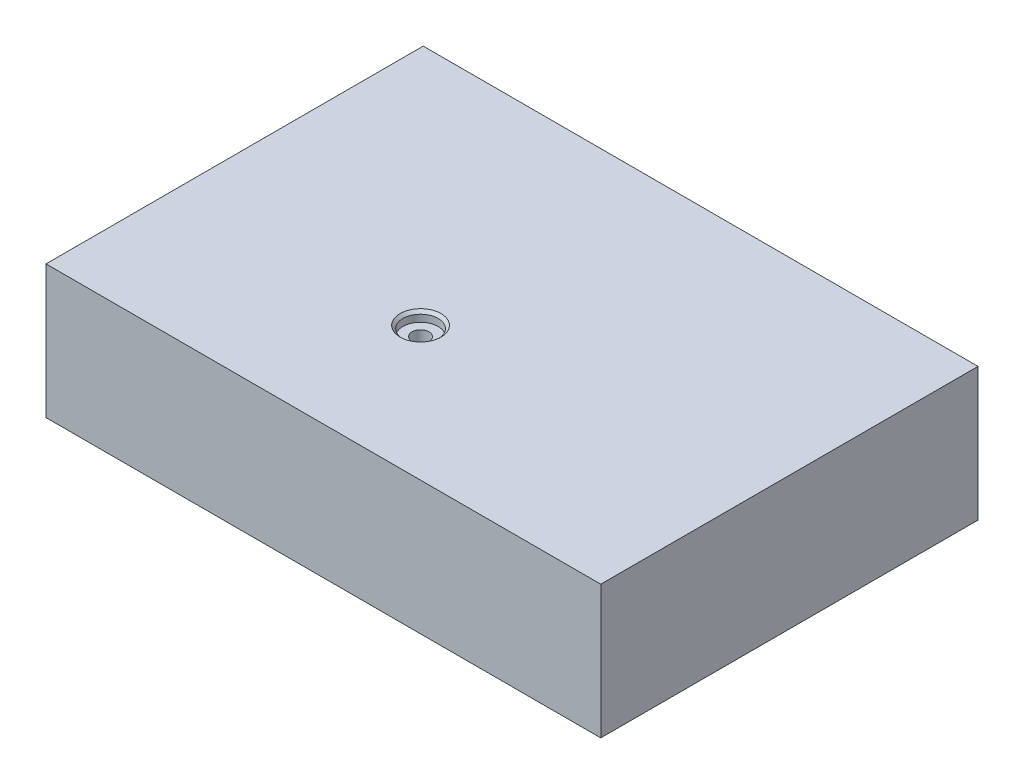
SolidWorks part; units mm, degrees
ref_plane "Front Plane" through (0, 0, 0) normal (0, 0, 1) x (1, 0, 0)
ref_plane "Top Plane" through (0, 0, 0) normal (0, 1, 0) x (1, 0, 0)
ref_plane "Right Plane" through (0, 0, 0) normal (1, 0, 0) x (0, 0, -1)
other "Configuration Table"
sketch "Sketch1" plane through (0, 0, 0) normal (0, 1, 0) x (1, 0, 0)
  line L1 (-81.1068, 38.9478) -> (43.8932, 38.9478)
  line L2 (-81.1068, 38.9478) -> (-81.1068, -46.0522)
  line L3 (-81.1068, -46.0522) -> (43.8932, -46.0522)
  line L4 (43.8932, 38.9478) -> (43.8932, -46.0522)
  dimension "D1" = 85
  dimension "D2" = 125
extrude "Boss-Extrude1" add sketch "Sketch1" along normal blind 30
hole_wizard "CBORE for #6 Binding Head Machine Screw1" positions "Sketch3" profile "Sketch2" counterbore size "#6" standard "Ansi Inch" end condition through all
sketch "Sketch3" plane through (0, 30, 0) normal (0, 1, 0) x (-1, 0, 0)
  point P0 (26.921, 15.8462)
sketch "Sketch2" plane through (-26.921, 30, 15.8462) normal (1, 0, 0) x (0, 0, 1)
  line L0 (0, 0) -> (0, 30)
  line L1 (0, 30) -> (1.8986, 30)
  line L3 (1.8986, 30) -> (1.8986, 2.2098)
  line L4 (3.9687, 2.2098) -> (1.8986, 2.2098)
  line L5 (3.9687, 2.2098) -> (3.9688, 0.635)
  line L6 (3.9688, 0.635) -> (4.6037, 0)
  line L7 (4.6037, 0) -> (0, 0)
  line L8 (-3.9688, 0.635) -> (-4.6037, 0) construction
  line L11 (0, -6.35) -> (0, 107.95) construction
  dimension "Thru Hole Dia." = 3.7973
  dimension "Thru Hole Depth" = 30
  dimension "C'Bore Dia." = 7.9375
  dimension "C'Bore Depth" = 2.2098
  dimension "Near C'Sink Dia." = 9.2075
  dimension "Near C'Sink Angle" = 90
